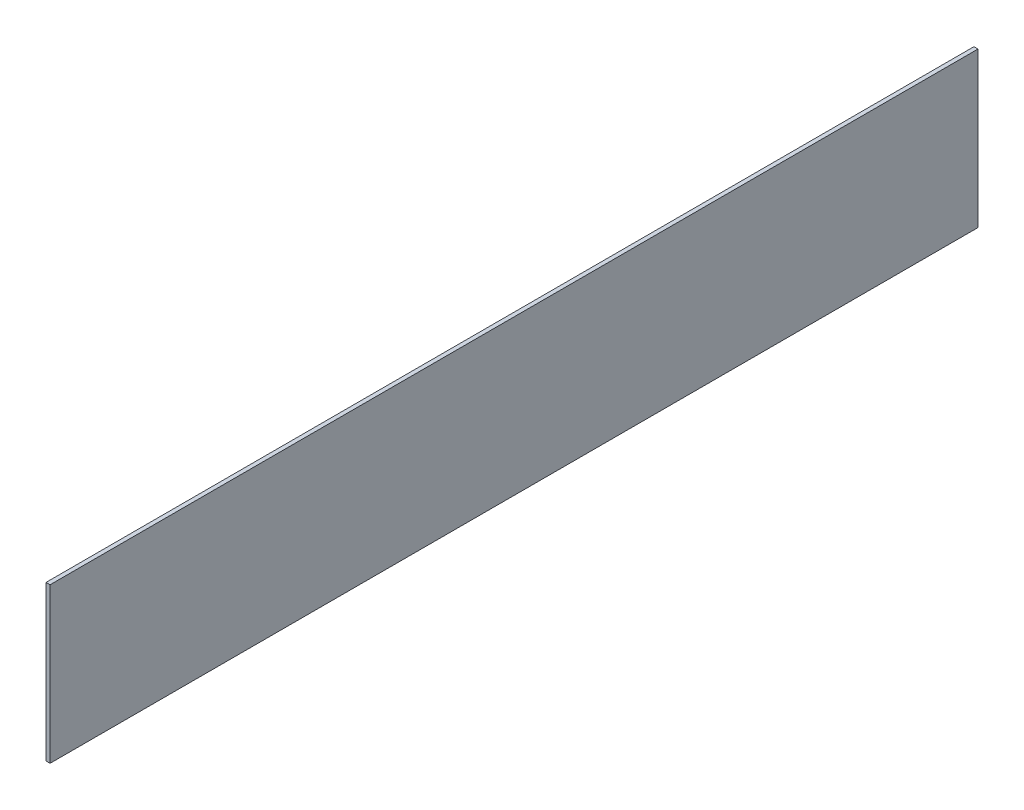
SolidWorks part; units mm, degrees
ref_plane "Front Plane" through (0, 0, 0) normal (0, 0, 1) x (1, 0, 0)
ref_plane "Top Plane" through (0, 0, 0) normal (0, 1, 0) x (1, 0, 0)
ref_plane "Right Plane" through (0, 0, 0) normal (1, 0, 0) x (0, 0, -1)
sketch "Sketch1" plane through (0, 0, 0) normal (1, 0, 0) x (0, 0, -1)
  line L1 (-228.6, 38.1) -> (228.6, 38.1)
  line L2 (-228.6, 38.1) -> (-228.6, -38.1)
  line L3 (-228.6, -38.1) -> (228.6, -38.1)
  line L4 (228.6, 38.1) -> (228.6, -38.1)
  line L5 (-228.6, 38.1) -> (228.6, -38.1) construction
  line L6 (-228.6, -38.1) -> (228.6, 38.1) construction
  point P0 (0, 0)
extrude "Boss-Extrude1" add sketch "Sketch1" along normal blind 2
